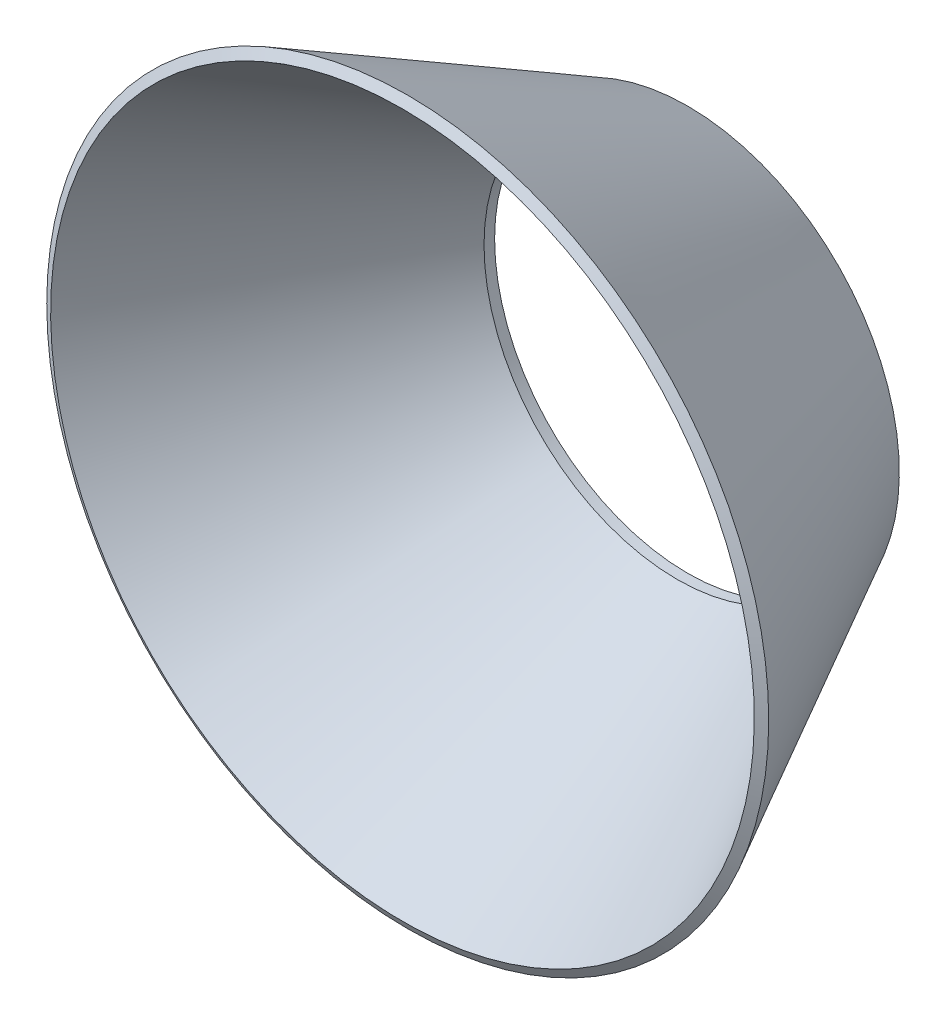
SolidWorks part; units mm, degrees
ref_plane "前视基准面" through (0, 0, 0) normal (0, 0, 1) x (1, 0, 0)
ref_plane "上视基准面" through (0, 0, 0) normal (0, 1, 0) x (1, 0, 0)
ref_plane "右视基准面" through (0, 0, 0) normal (1, 0, 0) x (0, 0, -1)
sketch "草图1" plane through (0, 0, 0) normal (0, 0, 1) x (1, 0, 0)
  circle A0 centre (0, 0) radius 100
  circle A1 centre (0, 0) radius 95
  dimension "D1" = 200
  dimension "D2" = 5
extrude "凸台-拉伸1" add sketch "草图1" along normal blind 70
sketch "草图2" plane through (0, 0, 0) normal (0, 0, -1) x (-1, 0, 0)
  circle A1 centre (0, 0) radius 100
  circle A2 centre (0, 0) radius 100
  dimension "D1" = 0
extrude "凸台-拉伸2" add sketch "草图2" along normal blind 5
sketch "草图5" plane through (0, 0, 0) normal (1, 0, 0) x (0, 0, -1)
  line L0 (-80, 85) -> (-71.3397, 80)
  line L1 (-71.3397, 80) -> (-75.3397, 73.0718)
  line L2 (-75.3397, 73.0718) -> (-179.2628, 133.0718)
  line L3 (-179.2628, 133.0718) -> (-175.2628, 140)
  line L4 (-175.2628, 140) -> (-80, 85)
  line L5 (-70, 100) -> (-70, 120.7373) construction
  line L7 (-70, 100) -> (-70, -100) construction
  line L8 (-71.3397, 80) -> (-177.2628, 136.5359)
  line L9 (0, 0) -> (-163.298, 0) construction
  dimension "D1" = 8
  dimension "D2" = 120
  dimension "D3" = 60
  dimension "D4" = 10
  dimension "D5" = 10
  dimension "D6" = 80
revolve "旋转1" add sketch "草图5" angle 360 about L9
sketch "草图6" plane through (0, 0, -5) normal (0, 0, -1) x (-1, 0, 0)
  circle A1 centre (0, 0) radius 100
  circle A2 centre (0, 0) radius 100
  dimension "D1" = 0
extrude "切除-拉伸1" cut sketch "草图6" against normal up to surface (75 mm away) up to face at (100, 0, 70)
ref_plane "基准面1" through (0, 0, 71.3397) normal (0, 0, -1) x (-1, 0, 0)
sketch "草图8" plane through (0, 0, 71.3397) normal (0, 0, -1) x (-1, 0, 0)
  circle A0 centre (0, 0) radius 80 construction
  circle A1 centre (0, 0) radius 80
  circle A2 centre (0, 0) radius 73.0718 construction
  circle A3 centre (0, 0) radius 73.0718
ref_plane "基准面2" through (0, 0, 75.3397) normal (0, 0, -1) x (-1, 0, 0)
extrude "凸台-拉伸3" add sketch "草图8" against normal up to surface (4 mm away) up to plane "基准面2"
